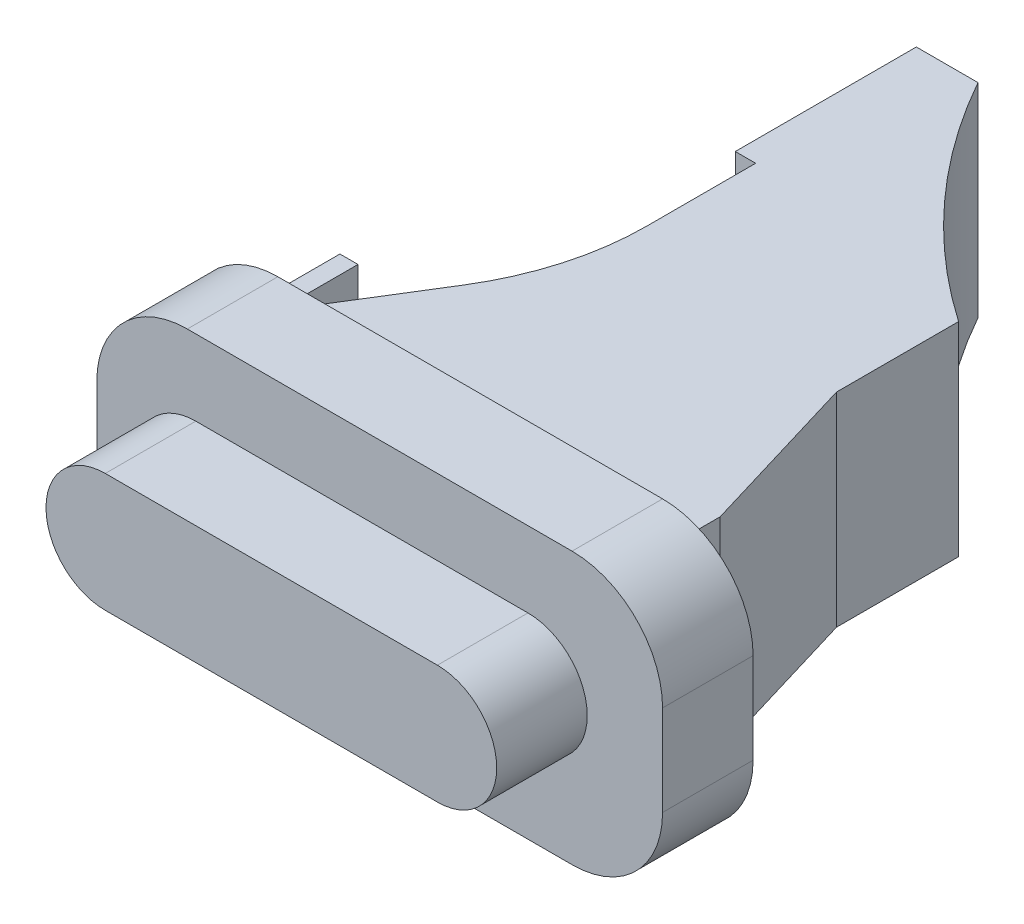
SolidWorks part; units mm, degrees
ref_plane "Front Plane" through (0, 0, 0) normal (0, 0, 1) x (1, 0, 0)
ref_plane "Top Plane" through (0, 0, 0) normal (0, 1, 0) x (1, 0, 0)
ref_plane "Right Plane" through (0, 0, 0) normal (1, 0, 0) x (0, 0, -1)
sketch "Sketch1" plane through (0, 0, 0) normal (0, 0, 1) x (1, 0, 0)
  line L1 (-7.5, 3) -> (7.5, 3)
  line L2 (-7.5, 3) -> (-7.5, -3)
  line L3 (-7.5, -3) -> (7.5, -3)
  line L4 (7.5, 3) -> (7.5, -3)
  line L5 (-7.5, 3) -> (7.5, -3) construction
  line L6 (-7.5, -3) -> (7.5, 3) construction
  point P0 (0, 0)
  dimension "D1" = 15
  dimension "D2" = 6
extrude "Boss-Extrude1" add sketch "Sketch1" along normal blind 2
sketch "Sketch2" plane through (0, 0, 2) normal (0, 0, 1) x (1, 0, 0)
  line L0 (-5.3128, 0.0205) -> (2.0252, 0.0205) construction
  line L1 (-5.3128, 1.3302) -> (2.0252, 1.3302)
  line L2 (-5.3128, -1.2892) -> (2.0252, -1.2892)
  arc A0 (-5.3128, 1.3302) -> (-5.3128, -1.2892) centre (-5.3128, 0.0205) ccw
  arc A1 (2.0252, -1.2892) -> (2.0252, 1.3302) centre (2.0252, 0.0205) ccw
  point P2 (-1.6438, 0.0205)
extrude "Boss-Extrude2" add sketch "Sketch2" along normal blind 2
sketch "Sketch3" plane through (0, 0, 0) normal (0, 1, 0) x (1, 0, 0)
  line L0 (7.5, 0) -> (-7.5, 0) construction
  line L1 (-5.267, 0.6593) -> (-4.0407, 2.642)
  line L2 (-3.1435, 5.7982) -> (-3.1435, 7.8852)
  line L3 (2.1273, 7.8852) -> (2.1273, 4.7149)
  line L4 (3.2287, 0) -> (3.2287, 1.0429)
  line L5 (2.1273, 4.7149) -> (3.2287, 1.0429)
  line L6 (-5.267, 0) -> (-5.267, 0.6593)
  line L7 (-1.1926, -2) -> (-1.1926, 1.9881) construction
  line L9 (-5.267, 0) -> (3.2287, 0)
  line L11 (-3.1435, 7.8852) -> (-3.1435, 12.1994)
  line L12 (-3.1435, 12.1994) -> (2.1273, 12.1994)
  line L16 (2.1273, 12.1994) -> (2.1273, 7.8852)
  arc A0 (-4.0407, 2.642) -> (-3.1435, 5.7982) centre (-9.1435, 5.7982) ccw
  dimension "D1" = 6
extrude "Boss-Extrude3" add sketch "Sketch3" along normal mid plane 4.5
sketch "Sketch4" plane through (7.5, 0, 0) normal (1, 0, 0) x (0, 0, -1)
  line L4 (0, -3) -> (0, 3)
  line L5 (0, 3) -> (-2, 3)
  line L6 (-2, 3) -> (-2, -3)
  line L7 (-2, -3) -> (0, -3)
  line L8 (0, -3) -> (0, 3)
  line L9 (0, 3) -> (-2, 3)
  line L10 (-2, 3) -> (-2, -3)
  line L11 (-2, -3) -> (0, -3)
  dimension "D1" = 0
extrude "Cut-Extrude1" cut sketch "Sketch4" against normal blind 2.5
sketch "Sketch6" [suppressed] plane through (0, 0, 4) normal (0, 0, 1) x (1, 0, 0)
  line L0 (2.7248, 0.4438) -> (3.6607, 0.4438) construction
  line L1 (2.1874, 1.4546) -> (2.0938, 1.4546) construction
  line L2 (0.5082, 0.2034) -> (0.5082, 0.0733) construction
  line L3 (2.0938, -1.1779) -> (2.1874, -1.1779) construction
  line L4 (3.6561, -0.1633) -> (2.7248, -0.1633) construction
  line L5 (-0.5835, 0.4438) -> (0.3524, 0.4438) construction
  line L6 (-1.1209, 1.4546) -> (-1.2145, 1.4546) construction
  line L7 (-2.8001, 0.2034) -> (-2.8001, 0.0733) construction
  line L8 (-1.2145, -1.1779) -> (-1.1209, -1.1779) construction
  line L9 (0.3478, -0.1633) -> (-0.5835, -0.1633) construction
  line L10 (-3.8918, 0.4438) -> (-2.956, 0.4438) construction
  line L11 (-4.4292, 1.4546) -> (-4.5228, 1.4546) construction
  line L12 (-6.1084, 0.2034) -> (-6.1084, 0.0733) construction
  line L13 (-4.5228, -1.1779) -> (-4.4292, -1.1779) construction
  line L14 (-2.9605, -0.1633) -> (-3.8918, -0.1633) construction
  line L15 (2.7248, 0.4438) -> (3.6607, 0.4438)
  line L16 (2.1874, 1.4546) -> (2.0938, 1.4546)
  line L17 (0.5082, 0.2034) -> (0.5082, 0.0733)
  line L18 (2.0938, -1.1779) -> (2.1874, -1.1779)
  line L19 (3.6561, -0.1633) -> (2.7248, -0.1633)
  line L20 (-0.5835, 0.4438) -> (0.3524, 0.4438)
  line L21 (-1.1209, 1.4546) -> (-1.2145, 1.4546)
  line L22 (-2.8001, 0.2034) -> (-2.8001, 0.0733)
  line L23 (-1.2145, -1.1779) -> (-1.1209, -1.1779)
  line L24 (0.3478, -0.1633) -> (-0.5835, -0.1633)
  line L25 (-3.8918, 0.4438) -> (-2.956, 0.4438)
  line L26 (-4.4292, 1.4546) -> (-4.5228, 1.4546)
  line L27 (-6.1084, 0.2034) -> (-6.1084, 0.0733)
  line L28 (-4.5228, -1.1779) -> (-4.4292, -1.1779)
  line L29 (-2.9605, -0.1633) -> (-3.8918, -0.1633)
  arc A0 (2.6631, 0.4874) -> (2.7248, 0.4438) centre (2.7248, 0.5092) ccw construction
  arc A1 (3.6607, 0.4438) -> (3.6899, 0.4686) centre (3.6562, 0.4787) ccw construction
  arc A2 (3.6899, 0.4686) -> (3.6857, 0.5561) centre (3.5093, 0.5038) ccw construction
  arc A3 (3.6857, 0.5561) -> (3.5485, 0.8134) centre (2.6037, 0.1445) ccw construction
  arc A4 (3.5485, -0.5368) -> (3.681, -0.2904) centre (2.6131, 0.1249) ccw construction
  arc A5 (3.681, -0.2904) -> (3.6908, -0.1925) centre (3.5095, -0.2237) ccw construction
  arc A6 (3.6908, -0.1925) -> (3.6561, -0.1633) centre (3.6561, -0.1984) ccw construction
  arc A7 (2.7248, -0.1633) -> (2.6631, -0.2069) centre (2.7248, -0.2287) ccw construction
  arc A8 (-0.6452, 0.4874) -> (-0.5835, 0.4438) centre (-0.5835, 0.5092) ccw construction
  arc A9 (0.3524, 0.4438) -> (0.3816, 0.4686) centre (0.3479, 0.4787) ccw construction
  arc A10 (0.3816, 0.4686) -> (0.3774, 0.5561) centre (0.201, 0.5038) ccw construction
  arc A11 (0.3774, 0.5561) -> (0.2402, 0.8134) centre (-0.7046, 0.1445) ccw construction
  arc A12 (0.2402, -0.5368) -> (0.3727, -0.2904) centre (-0.6952, 0.1249) ccw construction
  arc A13 (0.3727, -0.2904) -> (0.3825, -0.1925) centre (0.2012, -0.2237) ccw construction
  arc A14 (0.3825, -0.1925) -> (0.3478, -0.1633) centre (0.3478, -0.1984) ccw construction
  arc A15 (-0.5835, -0.1633) -> (-0.6452, -0.2069) centre (-0.5835, -0.2287) ccw construction
  arc A16 (-3.9535, 0.4874) -> (-3.8918, 0.4438) centre (-3.8918, 0.5092) ccw construction
  arc A17 (-2.956, 0.4438) -> (-2.9267, 0.4686) centre (-2.9604, 0.4787) ccw construction
  arc A18 (-2.9267, 0.4686) -> (-2.9309, 0.5561) centre (-3.1073, 0.5038) ccw construction
  arc A19 (-2.9309, 0.5561) -> (-3.0681, 0.8134) centre (-4.0129, 0.1445) ccw construction
  arc A20 (-3.0681, -0.5368) -> (-2.9356, -0.2904) centre (-4.0035, 0.1249) ccw construction
  arc A21 (-2.9356, -0.2904) -> (-2.9258, -0.1925) centre (-3.1071, -0.2237) ccw construction
  arc A22 (-2.9258, -0.1925) -> (-2.9605, -0.1633) centre (-2.9605, -0.1984) ccw construction
  arc A23 (-3.8918, -0.1633) -> (-3.9535, -0.2069) centre (-3.8918, -0.2287) ccw construction
  arc A24 (2.6631, 0.4874) -> (2.7248, 0.4438) centre (2.7248, 0.5092) ccw
  arc A25 (3.6607, 0.4438) -> (3.6899, 0.4686) centre (3.6562, 0.4787) ccw
  arc A26 (3.6899, 0.4686) -> (3.6857, 0.5561) centre (3.5093, 0.5038) ccw
  arc A27 (3.6857, 0.5561) -> (3.5485, 0.8134) centre (2.6037, 0.1445) ccw
  arc A28 (3.5485, -0.5368) -> (3.681, -0.2904) centre (2.6131, 0.1249) ccw
  arc A29 (3.681, -0.2904) -> (3.6908, -0.1925) centre (3.5095, -0.2237) ccw
  arc A30 (3.6908, -0.1925) -> (3.6561, -0.1633) centre (3.6561, -0.1984) ccw
  arc A31 (2.7248, -0.1633) -> (2.6631, -0.2069) centre (2.7248, -0.2287) ccw
  arc A32 (-0.6452, 0.4874) -> (-0.5835, 0.4438) centre (-0.5835, 0.5092) ccw
  arc A33 (0.3524, 0.4438) -> (0.3816, 0.4686) centre (0.3479, 0.4787) ccw
  arc A34 (0.3816, 0.4686) -> (0.3774, 0.5561) centre (0.201, 0.5038) ccw
  arc A35 (0.3774, 0.5561) -> (0.2402, 0.8134) centre (-0.7046, 0.1445) ccw
  arc A36 (0.2402, -0.5368) -> (0.3727, -0.2904) centre (-0.6952, 0.1249) ccw
  arc A37 (0.3727, -0.2904) -> (0.3825, -0.1925) centre (0.2012, -0.2237) ccw
  arc A38 (0.3825, -0.1925) -> (0.3478, -0.1633) centre (0.3478, -0.1984) ccw
  arc A39 (-0.5835, -0.1633) -> (-0.6452, -0.2069) centre (-0.5835, -0.2287) ccw
  arc A40 (-3.9535, 0.4874) -> (-3.8918, 0.4438) centre (-3.8918, 0.5092) ccw
  arc A41 (-2.956, 0.4438) -> (-2.9267, 0.4686) centre (-2.9604, 0.4787) ccw
  arc A42 (-2.9267, 0.4686) -> (-2.9309, 0.5561) centre (-3.1073, 0.5038) ccw
  arc A43 (-2.9309, 0.5561) -> (-3.0681, 0.8134) centre (-4.0129, 0.1445) ccw
  arc A44 (-3.0681, -0.5368) -> (-2.9356, -0.2904) centre (-4.0035, 0.1249) ccw
  arc A45 (-2.9356, -0.2904) -> (-2.9258, -0.1925) centre (-3.1071, -0.2237) ccw
  arc A46 (-2.9258, -0.1925) -> (-2.9605, -0.1633) centre (-2.9605, -0.1984) ccw
  arc A47 (-3.8918, -0.1633) -> (-3.9535, -0.2069) centre (-3.8918, -0.2287) ccw
  ellipse E0 centre (2.0788, 0.1385) end of major axis (1.7962, -0.5431) minor radius 0.6039 (2.6631, 0.4874) -> (2.1069, 0.8549) ccw construction
  ellipse E1 centre (2.0654, 0.1529) end of major axis (0.4226, -0.0922) minor radius 1.2925 (3.5485, 0.8134) -> (2.1874, 1.4546) ccw construction
  ellipse E2 centre (2.1562, 0.1542) end of major axis (0.5113, 0.2835) minor radius 1.2979 (2.0938, 1.4546) -> (0.5082, 0.2034) ccw construction
  ellipse E3 centre (2.1562, 0.1225) end of major axis (3.8011, 0.2518) minor radius 1.2979 (0.5082, 0.0733) -> (2.0938, -1.1779) ccw construction
  ellipse E4 centre (2.0654, 0.1238) end of major axis (0.4226, 0.3689) minor radius 1.2925 (2.1874, -1.1779) -> (3.5485, -0.5368) ccw construction
  ellipse E5 centre (2.0788, 0.1421) end of major axis (2.3614, -0.5396) minor radius 0.6039 (2.1666, -0.5777) -> (2.6631, -0.2069) ccw construction
  ellipse E6 centre (2.1349, 0.1385) end of major axis (2.1385, -0.5786) minor radius 0.6209 (2.1069, 0.8549) -> (2.1666, -0.5777) ccw construction
  ellipse E7 centre (-1.2295, 0.1385) end of major axis (-1.5121, -0.5431) minor radius 0.6039 (-0.6452, 0.4874) -> (-1.2015, 0.8549) ccw construction
  ellipse E8 centre (-1.2429, 0.1529) end of major axis (0.3999, 0.3981) minor radius 1.2925 (0.2402, 0.8134) -> (-1.1209, 1.4546) ccw construction
  ellipse E9 centre (-1.1521, 0.1542) end of major axis (-2.797, 0.2835) minor radius 1.2979 (-1.2145, 1.4546) -> (-2.8001, 0.2034) ccw construction
  ellipse E10 centre (-1.1521, 0.1225) end of major axis (0.4928, 0.2518) minor radius 1.2979 (-2.8001, 0.0733) -> (-1.2145, -1.1779) ccw construction
  ellipse E11 centre (-1.2429, 0.1238) end of major axis (0.3999, -0.1214) minor radius 1.2925 (-1.1209, -1.1779) -> (0.2402, -0.5368) ccw construction
  ellipse E12 centre (-1.2295, 0.1421) end of major axis (-0.9469, -0.5396) minor radius 0.6039 (-1.1417, -0.5777) -> (-0.6452, -0.2069) ccw construction
  ellipse E13 centre (-1.1734, 0.1385) end of major axis (-1.1698, -0.5786) minor radius 0.6209 (-1.2015, 0.8549) -> (-1.1417, -0.5777) ccw construction
  ellipse E14 centre (-4.5378, 0.1385) end of major axis (-4.8204, -0.5431) minor radius 0.6039 (-3.9535, 0.4874) -> (-4.5098, 0.8549) ccw construction
  ellipse E15 centre (-4.5512, 0.1529) end of major axis (-2.9084, 0.3981) minor radius 1.2925 (-3.0681, 0.8134) -> (-4.4292, 1.4546) ccw construction
  ellipse E16 centre (-4.4604, 0.1542) end of major axis (-6.1053, 0.2835) minor radius 1.2979 (-4.5228, 1.4546) -> (-6.1084, 0.2034) ccw construction
  ellipse E17 centre (-4.4604, 0.1225) end of major axis (-2.8155, 0.2518) minor radius 1.2979 (-6.1084, 0.0733) -> (-4.5228, -1.1779) ccw construction
  ellipse E18 centre (-4.5512, 0.1238) end of major axis (-6.194, 0.3689) minor radius 1.2925 (-4.4292, -1.1779) -> (-3.0681, -0.5368) ccw construction
  ellipse E19 centre (-4.5378, 0.1421) end of major axis (-4.2552, -0.5396) minor radius 0.6039 (-4.45, -0.5777) -> (-3.9535, -0.2069) ccw construction
  ellipse E20 centre (-4.4817, 0.1385) end of major axis (-4.4781, -0.5786) minor radius 0.6209 (-4.5098, 0.8549) -> (-4.45, -0.5777) ccw construction
  ellipse E21 centre (2.0788, 0.1385) end of major axis (1.7962, -0.5431) minor radius 0.6039 (2.6631, 0.4874) -> (2.1069, 0.8549) ccw
  ellipse E22 centre (2.0654, 0.1529) end of major axis (3.7082, 0.3981) minor radius 1.2925 (3.5485, 0.8134) -> (2.1874, 1.4546) ccw
  ellipse E23 centre (2.1562, 0.1542) end of major axis (0.5113, 0.2835) minor radius 1.2979 (2.0938, 1.4546) -> (0.5082, 0.2034) ccw
  ellipse E24 centre (2.1562, 0.1225) end of major axis (3.8011, 0.2518) minor radius 1.2979 (0.5082, 0.0733) -> (2.0938, -1.1779) ccw
  ellipse E25 centre (2.0654, 0.1238) end of major axis (0.4226, 0.3689) minor radius 1.2925 (2.1874, -1.1779) -> (3.5485, -0.5368) ccw
  ellipse E26 centre (2.0788, 0.1421) end of major axis (2.3614, -0.5396) minor radius 0.6039 (2.1666, -0.5777) -> (2.6631, -0.2069) ccw
  ellipse E27 centre (2.1349, 0.1385) end of major axis (2.1385, -0.5786) minor radius 0.6209 (2.1069, 0.8549) -> (2.1666, -0.5777) ccw
  ellipse E28 centre (-1.2295, 0.1385) end of major axis (-1.5121, -0.5431) minor radius 0.6039 (-0.6452, 0.4874) -> (-1.2015, 0.8549) ccw
  ellipse E29 centre (-1.2429, 0.1529) end of major axis (0.3999, 0.3981) minor radius 1.2925 (0.2402, 0.8134) -> (-1.1209, 1.4546) ccw
  ellipse E30 centre (-1.1521, 0.1542) end of major axis (-2.797, 0.2835) minor radius 1.2979 (-1.2145, 1.4546) -> (-2.8001, 0.2034) ccw
  ellipse E31 centre (-1.1521, 0.1225) end of major axis (0.4928, 0.2518) minor radius 1.2979 (-2.8001, 0.0733) -> (-1.2145, -1.1779) ccw
  ellipse E32 centre (-1.2429, 0.1238) end of major axis (-2.8857, 0.3689) minor radius 1.2925 (-1.1209, -1.1779) -> (0.2402, -0.5368) ccw
  ellipse E33 centre (-1.2295, 0.1421) end of major axis (-0.9469, -0.5396) minor radius 0.6039 (-1.1417, -0.5777) -> (-0.6452, -0.2069) ccw
  ellipse E34 centre (-1.1734, 0.1385) end of major axis (-1.1698, -0.5786) minor radius 0.6209 (-1.2015, 0.8549) -> (-1.1417, -0.5777) ccw
  ellipse E35 centre (-4.5378, 0.1385) end of major axis (-4.8204, -0.5431) minor radius 0.6039 (-3.9535, 0.4874) -> (-4.5098, 0.8549) ccw
  ellipse E36 centre (-4.5512, 0.1529) end of major axis (-2.9084, 0.3981) minor radius 1.2925 (-3.0681, 0.8134) -> (-4.4292, 1.4546) ccw
  ellipse E37 centre (-4.4604, 0.1542) end of major axis (-6.1053, 0.2835) minor radius 1.2979 (-4.5228, 1.4546) -> (-6.1084, 0.2034) ccw
  ellipse E38 centre (-4.4604, 0.1225) end of major axis (-2.8155, 0.2518) minor radius 1.2979 (-6.1084, 0.0733) -> (-4.5228, -1.1779) ccw
  ellipse E39 centre (-4.5512, 0.1238) end of major axis (-6.194, 0.3689) minor radius 1.2925 (-4.4292, -1.1779) -> (-3.0681, -0.5368) ccw
  ellipse E40 centre (-4.5378, 0.1421) end of major axis (-4.2552, -0.5396) minor radius 0.6039 (-4.45, -0.5777) -> (-3.9535, -0.2069) ccw
  ellipse E41 centre (-4.4817, 0.1385) end of major axis (-4.4781, -0.5786) minor radius 0.6209 (-4.5098, 0.8549) -> (-4.45, -0.5777) ccw
extrude "Cut-Extrude3" [suppressed] cut sketch "Sketch6" against normal blind 0.7
sketch "Sketch7" plane through (-3.1435, 0, 0) normal (-1, 0, 0) x (0, 0, 1)
  line L0 (-12.1994, -2.25) -> (-5.7982, -2.25) construction
  line L1 (-12.1994, 2.25) -> (-8.1994, 2.25)
  line L2 (-12.1994, 2.25) -> (-12.1994, -2.25)
  line L3 (-12.1994, -2.25) -> (-8.1994, -2.25)
  line L4 (-8.1994, 2.25) -> (-8.1994, -2.25)
  dimension "D1" = 4
extrude "Boss-Extrude4" add sketch "Sketch7" along normal blind 0.45
sketch "Sketch14" plane through (0, 0, 0) normal (0, 0, -1) x (-1, 0, 0)
  line L1 (4.767, 0.825) -> (5.267, 0.825)
  line L2 (4.767, 0.825) -> (4.767, -0.825)
  line L3 (4.767, -0.825) -> (5.267, -0.825)
  line L4 (5.267, 0.825) -> (5.267, -0.825)
  line L5 (5.267, 2.25) -> (5.267, -2.25) construction
  line L6 (4.767, 0) -> (7.8514, 0) construction
  dimension "D1" = 1.65
  dimension "D2" = 0.5
extrude "Cut-Extrude5" cut sketch "Sketch14" along normal blind 2
sketch "Sketch8" plane through (0, 0, 0) normal (0, 1, 0) x (1, 0, 0)
  line L0 (-7.5, 0) -> (-7.5, 3.371)
  line L1 (-7.5, 3.371) -> (-7.1, 3.371)
  line L2 (-7.1, 3.371) -> (-7.1, 0)
  line L3 (5, 0) -> (-7.5, 0) construction
  line L4 (-7.1, 0) -> (-7.5, 0)
  line L6 (-5.1, 3.371) -> (-5.5, 3.371)
  line L7 (-5.1, 3.371) -> (-5.1, 0)
  line L8 (-5.1, 0) -> (-5.5, 0)
  line L9 (-5.5, 3.371) -> (-5.5, 0)
  dimension "D1" = 0.4
  dimension "D2" = 1.6
  dimension "D3" = 0.4
extrude "Boss-Extrude5" add sketch "Sketch8" against normal mid plane 1.5
pattern_linear "LPattern1" [suppressed] count 2 spacing 10.75
sketch "Sketch11" plane through (0, 2.25, 0) normal (0, 1, 0) x (1, 0, 0)
  line L0 (2.1273, 12.1994) -> (-3.5935, 12.1994) construction
  line L2 (-2.2306, 12.1994) -> (2.1273, 12.1994)
  line L3 (2.1273, 12.1994) -> (2.1273, 7.4129)
  line L4 (2.1273, 4.7149) -> (2.1273, 12.1994) construction
  arc A0 (-2.2306, 12.1994) -> (2.1273, 7.4129) centre (10.2386, 19.1749) ccw
extrude "Cut-Extrude4" cut sketch "Sketch11" against normal up to surface (4.5 mm away)
sketch "Sketch12" plane through (0, 0, 0) normal (0, 1, 0) x (1, 0, 0)
  line L2 (-5.5, 0) -> (-7.1, 0)
  line L3 (-5.5, 0) -> (-5.5, 1.8877)
  line L4 (-5.5, 1.8877) -> (-7.1, 1.8877)
  line L5 (-7.1, 0) -> (-7.1, 1.8877)
  line L6 (-7.1, 0) -> (-7.1, 3.371) construction
extrude "Boss-Extrude10" add sketch "Sketch12" against normal mid plane 1.5
sketch "Sketch13" [suppressed] plane through (0, -6, 0) normal (0, -1, 0) x (1, 0, 0)
  line L0 (-7.1, 0) -> (-7.1, -2.7203) construction
  line L1 (-7.1, -1.598) -> (-5.5, -1.598)
  line L2 (-7.1, -1.598) -> (-7.1, 0)
  line L3 (-7.1, 0) -> (-5.5, 0)
  line L4 (-5.5, -1.598) -> (-5.5, 0)
  line L5 (-5.5, -1.598) -> (-7.1, -1.598) construction
extrude "Boss-Extrude11" [suppressed] add sketch "Sketch13" against normal up to surface (1.25 mm away)
fillet "Fillet1" radius 2 4 edges at (-7.5, 3, 1) (-7.5, -3, 1) (5, -3, 1) (5, 3, 1)
